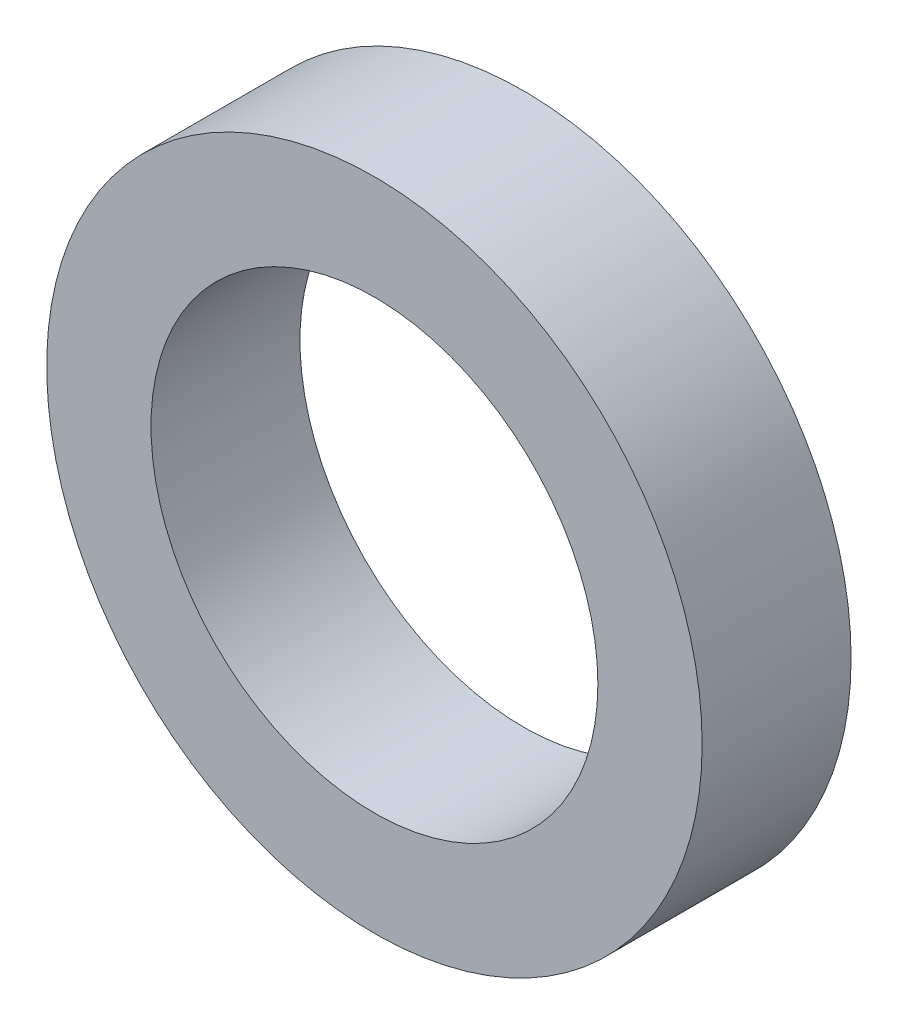
SolidWorks part; units mm, degrees
ref_plane "Front Plane" through (0, 0, 0) normal (0, 0, 1) x (1, 0, 0)
ref_plane "Top Plane" through (0, 0, 0) normal (0, 1, 0) x (1, 0, 0)
ref_plane "Right Plane" through (0, 0, 0) normal (1, 0, 0) x (0, 0, -1)
sketch "Sketch1" plane through (0, 0, 0) normal (0, 0, 1) x (1, 0, 0)
  circle A0 centre (0, 0) radius 22
  circle A1 centre (0, 0) radius 15
  dimension "D1" = 44
  dimension "D2" = 30
extrude "Boss-Extrude1" add sketch "Sketch1" along normal blind 10
